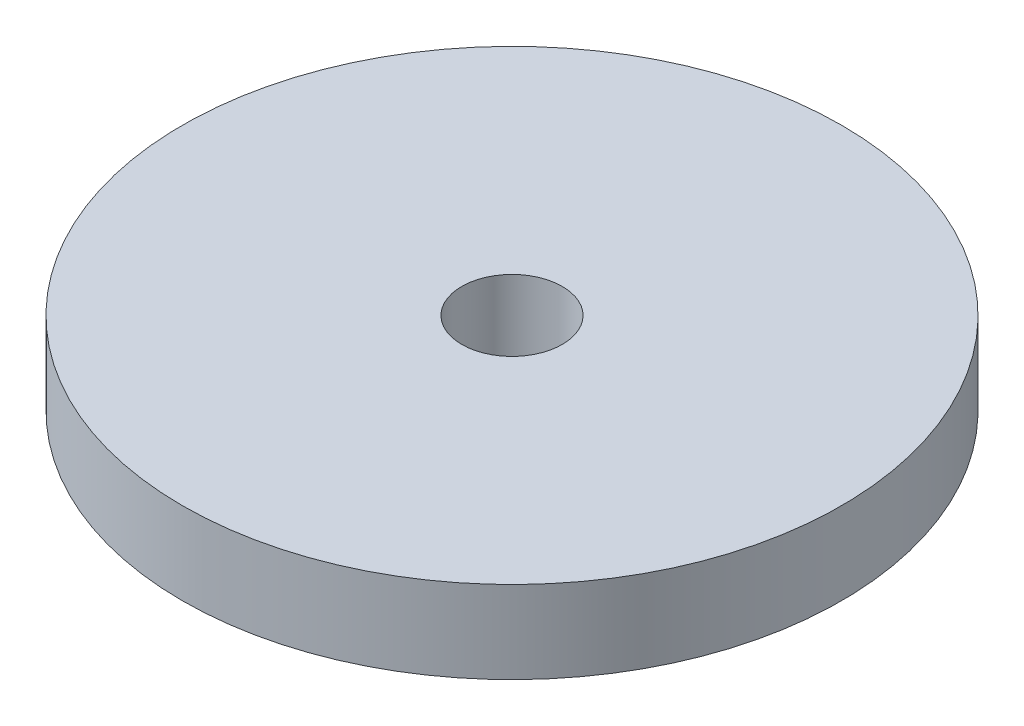
SolidWorks part; units mm, degrees
ref_plane "Спереди" through (0, 0, 0) normal (0, 0, 1) x (1, 0, 0)
ref_plane "Сверху" through (0, 0, 0) normal (0, 1, 0) x (1, 0, 0)
ref_plane "Справа" through (0, 0, 0) normal (1, 0, 0) x (0, 0, -1)
sketch "Эскиз1" plane through (0, 0, 0) normal (0, 1, 0) x (1, 0, 0)
  circle A0 centre (0, 0) radius 40
  circle A1 centre (0, 0) radius 6.1
  dimension "D1" = 80
  dimension "D2" = 12.2
extrude "Бобышка-Вытянуть1" add sketch "Эскиз1" along normal blind 10
